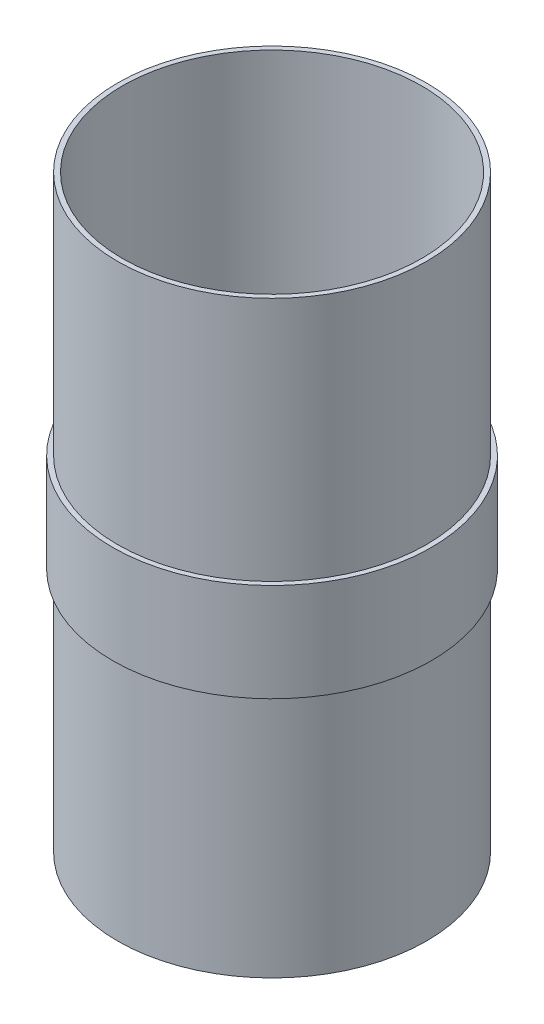
SolidWorks part; units mm, degrees
other "Marcação1"
sketch "Esboço5" plane through (-34.5, 110, -34.5) normal (-0.0418, 0.9983, -0.0408) x (0.9924, 0.0462, 0.1144)
material "Plástico personalizado (1)"
ref_plane "Plano frontal" through (0, 0, 0) normal (0, 0, 1) x (1, 0, 0)
ref_plane "Plano superior" through (0, 0, 0) normal (0, 1, 0) x (1, 0, 0)
ref_plane "Plano direito" through (0, 0, 0) normal (1, 0, 0) x (0, 0, -1)
sketch "Esboço1" plane through (0, 0, 0) normal (0, 1, 0) x (1, 0, 0)
  circle A0 centre (0, 0) radius 31.5
  circle A1 centre (0, 0) radius 30.5
extrude "Ressalto-extrusão1" add sketch "Esboço1" along normal blind 50 contours A1 | A0
sketch "Esboço2" plane through (0, 50, 0) normal (0, 1, 0) x (1, 0, 0)
  circle A0 centre (0, 0) radius 32.5
  circle A1 centre (0, 0) radius 30.5
extrude "Ressalto-extrusão2" add sketch "Esboço2" along normal blind 20 separate body contours A1 | A0
sketch "Esboço3" plane through (0, 70, 0) normal (0, 1, 0) x (1, 0, 0)
  circle A0 centre (0, 0) radius 30.5
  circle A1 centre (0, 0) radius 31.5
extrude "Ressalto-extrusão3" add sketch "Esboço3" along normal blind 50 separate body contours A1 | A0
sketch "Esboço6" plane through (0, 70, 0) normal (0, 1, 0) x (1, 0, 0)
  circle A0 centre (0, 0) radius 30.5
extrude "Ressalto-extrusão4" add sketch "Esboço6" against normal blind 5
combine bodies "Combinar3" operation type add bodies to combine 101 115
